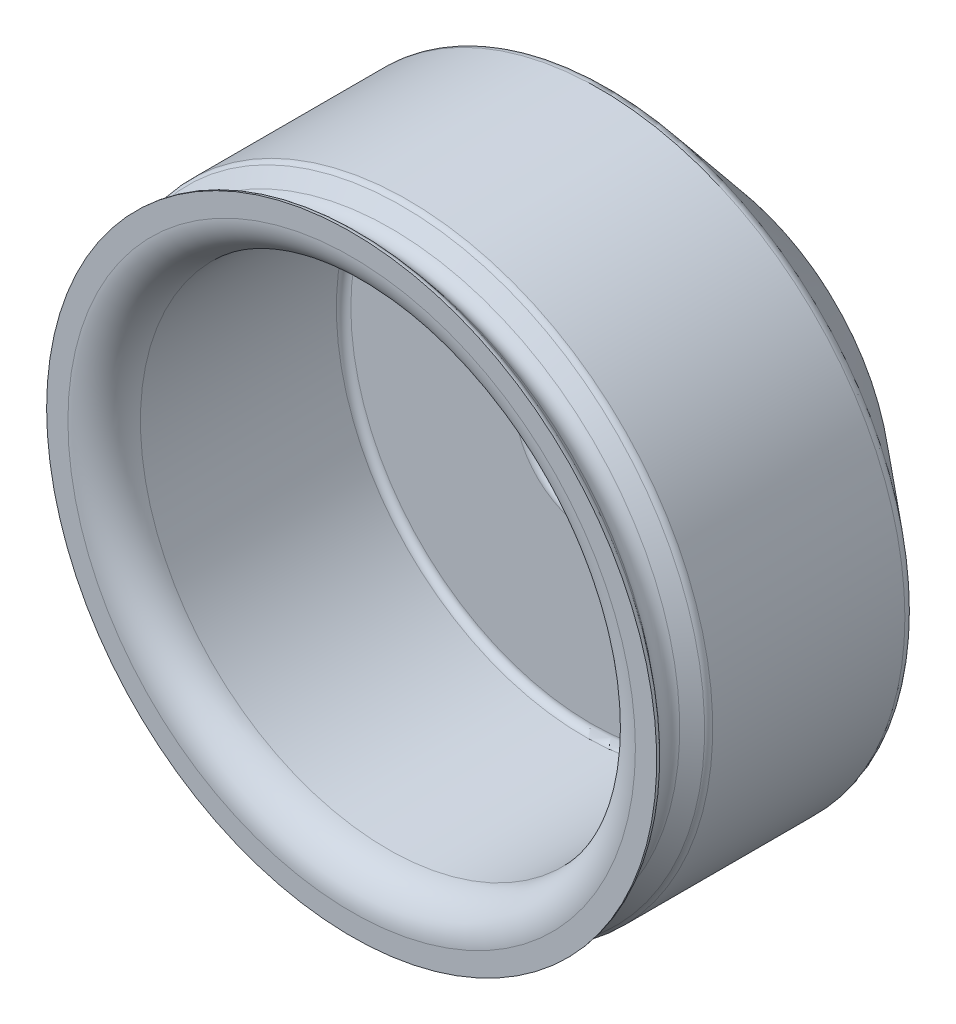
SolidWorks part; units mm, degrees
ref_plane "Front Plane" through (0, 0, 0) normal (0, 0, 1) x (1, 0, 0)
ref_plane "Top Plane" through (0, 0, 0) normal (0, 1, 0) x (1, 0, 0)
ref_plane "Right Plane" through (0, 0, 0) normal (1, 0, 0) x (0, 0, -1)
sketch "Sketch1" plane through (0, 0, 0) normal (0, 0, 1) x (1, 0, 0)
  line L0 (-1.6184, 1.4859) -> (1.6184, 1.4859)
  circle A0 centre (0, 0) radius 13.6525
  arc A1 (-1.6184, 1.4859) -> (1.6184, 1.4859) centre (0, 0) ccw
  point P6 (0, -2.1971)
  dimension "D1" = 27.305
  dimension "D2" = 4.3942
  dimension "D3" = 3.683
extrude "Boss-Extrude1" add sketch "Sketch1" along normal blind 3.175
sketch "Sketch2" plane through (0, 0, 3.175) normal (0, 0, 1) x (1, 0, 0)
  circle A0 centre (0, 0) radius 13.6525
  circle A1 centre (0, 0) radius 13.6525 construction
  circle A2 centre (0, 0) radius 3.81
  dimension "D1" = 7.62
extrude "Boss-Extrude2" add sketch "Sketch2" along normal blind 3.175
sketch "Sketch5" plane through (0, 0, 0) normal (1, 0, 0) x (0, 0, -1)
  line L0 (0, 13.6525) -> (-19.558, 13.6525)
  line L1 (-19.558, 13.6525) -> (-19.558, 16.8275)
  line L2 (-19.2516, 16.6846) -> (-18.6253, 15.9383)
  line L3 (-17.3997, 15.9383) -> (-16.7734, 16.6846)
  line L4 (-16.467, 16.8275) -> (0, 16.8275)
  line L5 (0, 16.8275) -> (0, 13.6525)
  line L6 (-6.35, 13.6525) -> (-6.35, -13.6525) construction
  line L7 (0, 0) -> (-13.419, 0) construction
  line L8 (0, -13.6525) -> (0, 13.6525) construction
  arc A0 (-19.558, 16.8275) -> (-19.2516, 16.6846) centre (-19.558, 16.4275) cw
  arc A1 (-18.6253, 15.9383) -> (-17.3997, 15.9383) centre (-18.0125, 16.4525) ccw
  arc A2 (-16.7734, 16.6846) -> (-16.467, 16.8275) centre (-16.467, 16.4275) cw
  point P20 (-18.0125, 15.6525)
  dimension "D1" = 0.4
  dimension "D2" = 0.8
  dimension "D3" = 40
  dimension "D4" = 13.208
  dimension "D5" = 3.175
  dimension "D6" = 2
revolve "Revolve1" add sketch "Sketch5" angle 360 about L7
fillet "Fillet1" radius 0.4 5 edges at (0, -2.1971, 3.175) (0, 1.4859, 3.175) (3.81, 0, 3.175) (3.81, 0, 6.35) (13.6525, 0, 6.35)
sketch "Sketch7" plane through (0, 0, 0) normal (0, 1, 0) x (1, 0, 0)
  line L0 (-16.8275, -5.588) -> (-10.168, 0)
  line L1 (-16.8275, 0) -> (-16.8275, -16.467) construction
  line L2 (16.8275, 0) -> (-16.8275, 0) construction
  line L3 (-10.168, 0) -> (-16.8275, 0)
  line L4 (-16.8275, 0) -> (-16.8275, -5.588)
  line L5 (0, 0) -> (0, -9.7273) construction
  dimension "D1" = 40
  dimension "D2" = 5.588
revolve "Cut-Revolve1" cut sketch "Sketch7" angle 360 about L5
fillet "Fillet3" radius 2 1 edges at (-13.6525, 0, 19.558)
fillet "Fillet6" radius 0.6 4 edges at (0, -2.1971, 0) (0, 1.4859, 0) (-10.168, 0, 0) (-16.8275, 0, 5.588)
